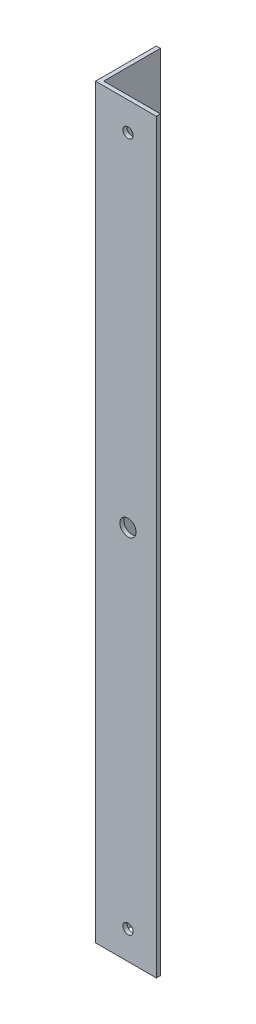
SolidWorks part; units mm, degrees
ref_plane "正面" through (0, 0, 0) normal (0, 0, 1) x (1, 0, 0)
ref_plane "平面" through (0, 0, 0) normal (0, 1, 0) x (1, 0, 0)
ref_plane "右側面" through (0, 0, 0) normal (1, 0, 0) x (0, 0, -1)
sketch "ｽｹｯﾁ1" plane through (0, 0, 0) normal (0, 1, 0) x (1, 0, 0)
  line L1 (0, 0) -> (15, 0)
  line L2 (0, 0) -> (0, -1)
  line L3 (0, -1) -> (15, -1)
  line L4 (15, 0) -> (15, -1)
  dimension "D1" = 15
  dimension "D2" = 1
sketch "ｽｹｯﾁ2" plane through (0, 0, 0) normal (0, 1, 0) x (1, 0, 0)
extrude "ﾎﾞｽ - 押し出し1" add sketch "ｽｹｯﾁ1" along normal blind 184
sketch "ｽｹｯﾁ3" plane through (0, 0, 0) normal (0, 0, -1) x (-1, 0, 0)
  line L1 (0, 184) -> (-1, 184)
  line L2 (0, 184) -> (0, 0)
  line L3 (0, 0) -> (-1, 0)
  line L4 (-1, 184) -> (-1, 0)
  dimension "D1" = 1
  dimension "D2" = 184
extrude "ﾎﾞｽ - 押し出し2" add sketch "ｽｹｯﾁ3" along normal blind 14
hole_wizard "M3x0.5 ねじ穴2" positions "ｽｹｯﾁ6" profile "ｽｹｯﾁ7" tap size "M3x0.5" standard "JIS" end condition through all
sketch "ｽｹｯﾁ6" plane through (0, 0, 1) normal (0, 0, 1) x (1, 0, 0)
  line L0 (15, 184) -> (15, 0) construction
  line L1 (8.25, 0) -> (-8.25, 0) construction
  line L2 (0, 184) -> (15, 184) construction
  point P0 (8, 7)
  point P2 (8, 177)
  dimension "D1" = 7
  dimension "D2" = 7
  dimension "D3" = 7
  dimension "D4" = 7
sketch "ｽｹｯﾁ7" plane through (8, 7, 1) normal (1, 0, 0) x (0, -1, 0)
  line L0 (0, 0) -> (0, 15)
  line L1 (0, 15) -> (1.25, 15)
  line L2 (1.25, 15) -> (1.25, 0)
  line L5 (1.25, 0) -> (0, 0)
  line L11 (0, -6.35) -> (0, 107.95) construction
  dimension "次ｻｰﾌｪｽまでのねじ下穴ﾄﾞﾘﾙ直径" = 2.5
  dimension "次ｻｰﾌｪｽまでのねじ下穴ﾄﾞﾘﾙの深さ" = 15
cosmetic thread "穴のねじ山3" parameters "D2"=3
cosmetic thread "穴のねじ山4" parameters "D2"=3
sketch "ｽｹｯﾁ8" plane through (0, 0, 1) normal (0, 0, 1) x (1, 0, 0)
  line L0 (15, 184) -> (15, 0) construction
  circle A0 centre (8, 92.6802) radius 2
  dimension "D1" = 4
  dimension "D2" = 7
extrude "ｶｯﾄ - 押し出し1" cut sketch "ｽｹｯﾁ8" against normal blind 10
